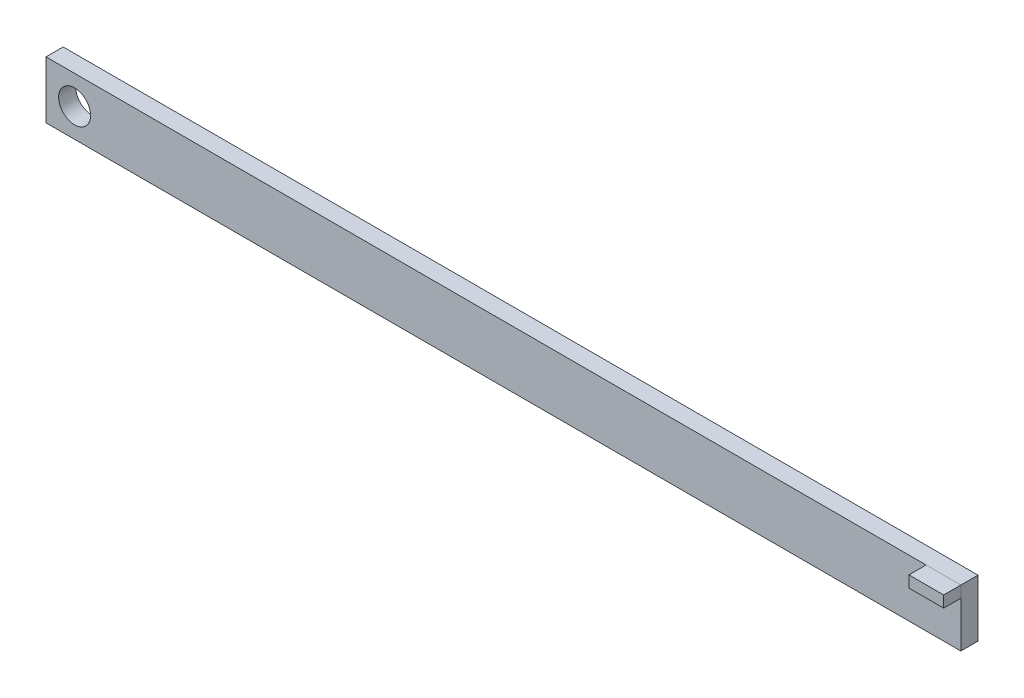
SolidWorks part; units mm, degrees
ref_plane "Front Plane" through (0, 0, 0) normal (0, 0, 1) x (1, 0, 0)
ref_plane "Top Plane" through (0, 0, 0) normal (0, 1, 0) x (1, 0, 0)
ref_plane "Right Plane" through (0, 0, 0) normal (1, 0, 0) x (0, 0, -1)
ref_plane "Plane1" through (0, 0, 89.9) normal (0, 0, 1) x (1, 0, 0)
sketch "Sketch1" plane through (0, 0, 89.9) normal (0, 0, 1) x (1, 0, 0)
  line L0 (65, 16) -> (220, 16)
  line L3 (65, 26) -> (220, 26)
  line L4 (220, 16) -> (220, 26)
  line L7 (65, 26) -> (60, 26)
  line L8 (60, 16) -> (60, 26)
  line L9 (65, 16) -> (60, 16)
  arc A0 (65, 18.2) -> (65, 23.8) centre (65, 21) ccw
  arc A1 (65, 18.2) -> (65, 23.8) centre (65, 21) ccw
  arc A2 (65, 23.8) -> (65, 18.2) centre (65, 21) ccw
  arc A3 (65, 23.8) -> (65, 18.2) centre (65, 21) ccw
  point P0 (65, 21)
  dimension "D1" = 155
  dimension "D2" = 10
  dimension "D3" = 5
  dimension "D4" = 5
extrude "Boss-Extrude1" add sketch "Sketch1" along normal blind 3
sketch "Sketch2" plane through (0, 0, 92.9) normal (0, 0, 1) x (1, 0, 0)
  line L0 (213.9221, 24) -> (220, 24)
  line L1 (220, 26) -> (220, 24)
  line L2 (213.9221, 26) -> (213.9221, 24)
  line L3 (220, 26) -> (213.9221, 26)
extrude "Boss-Extrude2" add sketch "Sketch2" along normal blind 3 separate body
